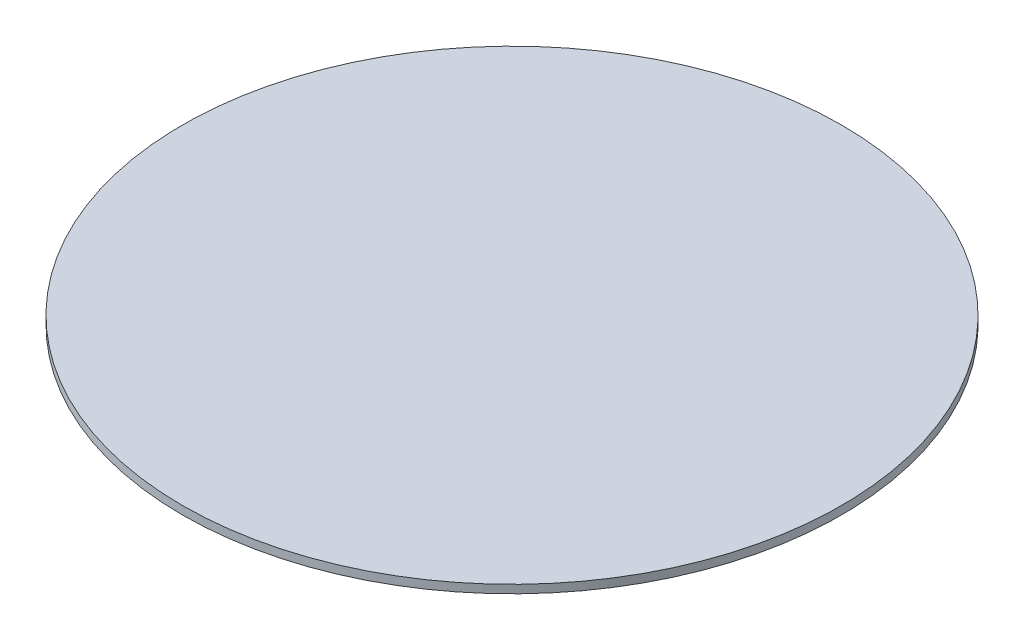
SolidWorks part; units mm, degrees
material "1060-H12"
ref_plane "Płaszczyzna przednia" through (0, 0, 0) normal (0, 0, 1) x (1, 0, 0)
ref_plane "Płaszczyzna górna" through (0, 0, 0) normal (0, 1, 0) x (1, 0, 0)
ref_plane "Płaszczyzna prawa" through (0, 0, 0) normal (1, 0, 0) x (0, 0, -1)
sketch "Szkic1" plane through (0, 0, 0) normal (0, 1, 0) x (1, 0, 0)
  circle A0 centre (0, 0) radius 12
extrude "Dodanie-wyciągnięcie1" add sketch "Szkic1" along normal blind 0.3
